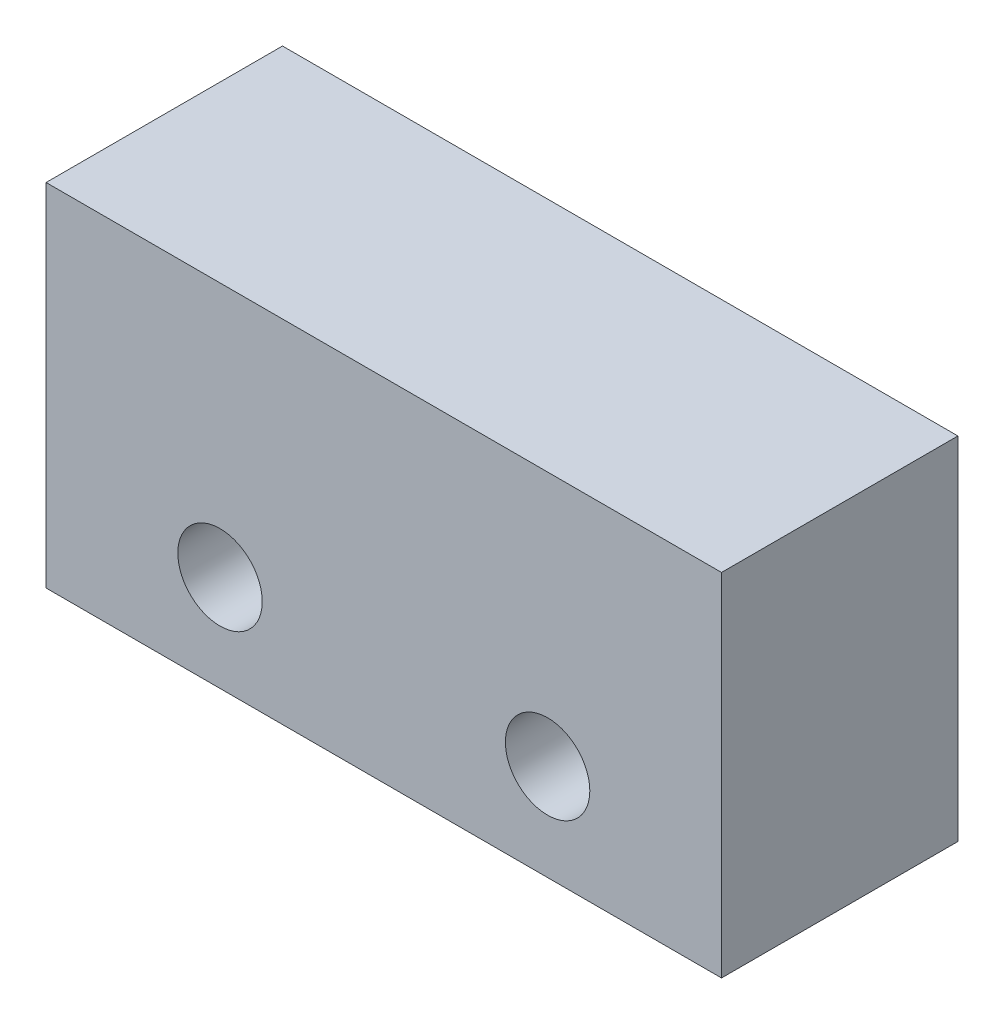
SolidWorks part; units mm, degrees
ref_plane "前视基准面" through (0, 0, 0) normal (0, 0, 1) x (1, 0, 0)
ref_plane "上视基准面" through (0, 0, 0) normal (0, 1, 0) x (1, 0, 0)
ref_plane "右视基准面" through (0, 0, 0) normal (1, 0, 0) x (0, 0, -1)
sketch "草图1" plane through (0, 0, 0) normal (0, 0, 1) x (1, 0, 0)
  line B0 (0, 10.4) -> (0, 0)
  line B1 (20, 10.4) -> (0, 10.4)
  line B2 (20, 0) -> (20, 10.4)
  line B3 (0, 0) -> (20, 0)
  circle B4 centre (5.15, 2.85) radius 1.25
  circle B5 centre (14.85, 2.85) radius 1.25
sketch_block_instance "块1-1"
sketch_block "块1"
extrude "凸台-拉伸1" add sketch "草图1" along normal blind 7
